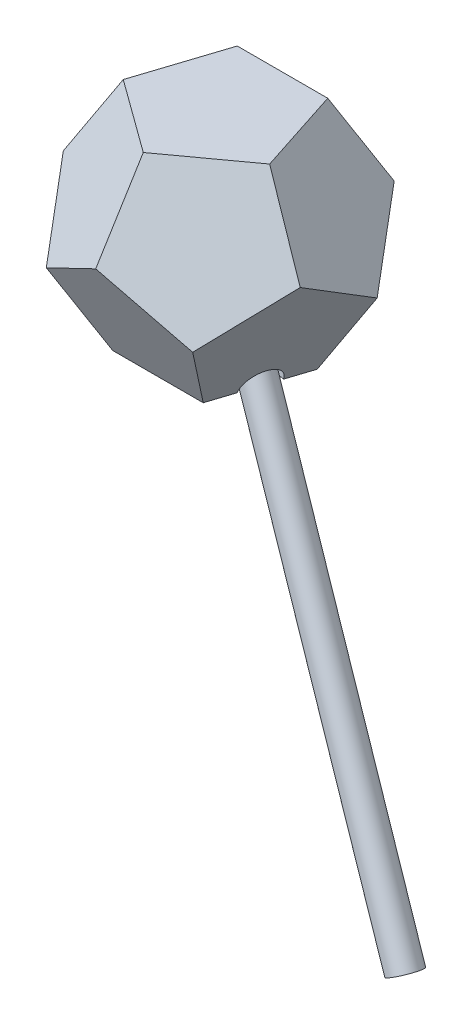
SolidWorks part; units mm, degrees
ref_plane "Front Plane" through (0, 0, 0) normal (0, 0, 1) x (1, 0, 0)
ref_plane "Top Plane" through (0, 0, 0) normal (0, 1, 0) x (1, 0, 0)
ref_plane "Right Plane" through (0, 0, 0) normal (1, 0, 0) x (0, 0, -1)
sketch "Sketch1" plane through (0, 0, 0) normal (0, 1, 0) x (1, 0, 0)
  line L1 (0, 17.013) -> (-16.1803, 5.2573)
  line L2 (-16.1803, 5.2573) -> (-10, -13.7638)
  line L3 (-10, -13.7638) -> (10, -13.7638)
  line L4 (10, -13.7638) -> (16.1803, 5.2573)
  line L5 (16.1803, 5.2573) -> (0, 17.013)
  circle A0 centre (0, 0) radius 13.7638 construction
  dimension "D1" = 20
extrude "Boss-Extrude1" add sketch "Sketch1" along normal blind 44.54 draft 26.57
ref_plane "Plane3" through (0, 22.27, 0) normal (0, 1, 0) x (1, 0, 0)
sketch "Sketch18" plane through (0, 22.27, 0) normal (0, 1, 0) x (1, 0, 0)
  line L0 (0, 0) -> (0, 44.5462)
  line L1 (0, 44.5462) -> (-42.3659, 13.7655) construction
  line L2 (42.3659, 13.7655) -> (0, 44.5462) construction
  line L3 (0, 0) -> (3.1668, 9.7464)
  line L4 (10, -13.7638) -> (16.1803, 5.2573) construction
sketch "Sketch2" plane through (0, 44.54, 0) normal (0, 1, 0) x (1, 0, 0)
  line L1 (0, -17.013) -> (16.1803, -5.2573)
  line L2 (16.1803, -5.2573) -> (10, 13.7638)
  line L3 (10, 13.7638) -> (-10, 13.7638)
  line L4 (-10, 13.7638) -> (-16.1803, -5.2573)
  line L5 (-16.1803, -5.2573) -> (0, -17.013)
  circle A0 centre (0, 0) radius 13.7638 construction
  dimension "D1" = 20
extrude "Cut-Extrude1" cut sketch "Sketch2" against normal blind 44.54 draft 26.57 flip side to cut
ref_plane "Plane1" through (3.6175, -6.1551, 1.1754) normal (0.5, -0.8507, 0.1624) x (0.4408, 0.0885, -0.8932)
sketch "Sketch3" plane through (3.6175, -6.1551, 1.1754) normal (0.5, -0.8507, 0.1624) x (0.4408, 0.0885, -0.8932)
  line L0 (-7.8859, 13.2251) -> (11.8286, 9.8577) construction
  circle A0 centre (1.9714, 11.5414) radius 4.05
  dimension "D1" = 8.1
extrude "Cut-Extrude2" cut sketch "Sketch3" against normal blind 35 contours A0
sketch "Sketch4" plane through (-13.8812, 23.6185, -4.5103) normal (0.5, -0.8507, 0.1624) x (0.866, 0.4911, -0.0938)
  circle A0 centre (10.9378, 4.1778) radius 3.2928
extrude "Boss-Extrude2" add sketch "Sketch4" along normal blind 130
sketch "Sketch5" [suppressed] plane through (51.1142, -86.9691, 16.608) normal (0.5, -0.8507, 0.1624) x (0.866, 0.4911, -0.0938)
  point P0 (10.9378, 4.1778)
  point P1 (24.3327, -4.2864)
sketch "Sketch6" plane through (-6.4716, -5.5062, -8.9074) normal (-0.5257, -0.4473, -0.7236) x (-0.8507, 0.2764, 0.4472)
  line L0 (-5.2301, 8.173) -> (2.5982, 32.2619) construction
  line L1 (2.5982, 32.2619) -> (16.8638, 27.6259) construction
  line L2 (16.8638, 27.6259) -> (9.0355, 3.537) construction
  line L3 (-7.6077, 8.9457) -> (11.4131, 2.7644) construction
  line L4 (11.4149, 35.1253) -> (23.1714, 18.9448) construction
  line L5 (1.3421, 28.3966) -> (15.6077, 23.7606)
  line L6 (15.6077, 23.7606) -> (10.9717, 9.495)
  line L7 (10.9717, 9.495) -> (-3.2939, 14.131)
  line L8 (-3.2939, 14.131) -> (1.3421, 28.3966)
  line L9 (6.1548, 18.9465) -> (-7.6077, 28.9473) construction
  line L10 (11.4149, 35.1253) -> (6.1548, 18.9465) construction
  line L11 (6.1548, 18.9465) -> (-7.6077, 8.9457) construction
  line L12 (-0.9759, 21.2638) -> (13.2897, 16.6278) construction
  dimension "D1" = 15
  dimension "D2" = 2.5
  dimension "D3" = 15
ref_plane "Plane2" through (-9.4711, 16.1166, -3.0773) normal (-0.4999, 0.8507, -0.1624) x (0.8661, 0.4911, -0.0938)
sketch "Sketch7" plane through (-10.4712, -5.5062, 3.4023) normal (-0.8506, -0.4473, 0.2764) x (0.2446, 0.1286, 0.961)
  line L0 (2.8652, 19.7147) -> (-12.3923, 27.2443) construction
  line L1 (2.8652, 19.7147) -> (-9.0106, 7.5307) construction
  line L2 (10.7815, 4.6542) -> (2.8652, 19.7147) construction
  line L3 (-9.0106, 7.5307) -> (10.7815, 4.6542) construction
  line L4 (-5.1697, 30.4822) -> (-7.9023, 11.6798)
  line L5 (-7.9023, 11.6798) -> (10.9001, 8.9472)
  line L6 (10.9001, 8.9472) -> (13.6328, 27.7496)
  line L7 (13.6328, 27.7496) -> (-5.1697, 30.4822)
  line L8 (2.8652, 19.7147) -> (5.3119, 36.5495) construction
  circle A0 centre (2.8652, 19.7147) radius 9.5 construction
  dimension "D1" = 19
sketch "Sketch8" plane through (0, -5.5062, 11.0101) normal (0, -0.4473, 0.8944) x (1, 0, 0)
  line L0 (0, 36.9335) -> (0, 19.9204) construction
  line L1 (0, 19.9204) -> (-10, 6.1564) construction
  line L2 (10, 6.1564) -> (0, 19.9204) construction
sketch "Sketch10" plane through (10.4712, -5.5062, 3.4023) normal (0.8506, -0.4473, 0.2764) x (0.2446, -0.1286, -0.961)
  line L0 (-5.3119, 36.5495) -> (-2.865, 19.7133) construction
  line L1 (-2.865, 19.7133) -> (-10.7815, 4.6542) construction
  line L2 (-2.865, 19.7133) -> (9.0106, 7.5307) construction
sketch "Sketch11" plane through (6.4716, -5.5062, -8.9074) normal (0.5257, -0.4473, -0.7236) x (-0.8507, -0.2764, -0.4472)
  line L0 (-11.4149, 35.1253) -> (-6.1567, 18.9451) construction
  line L1 (-6.1567, 18.9451) -> (-11.4131, 2.7644) construction
  line L2 (-6.1567, 18.9451) -> (7.6077, 8.9457) construction
sketch "Sketch12" plane through (0, 14.4173, -28.8284) normal (0, 0.4473, -0.8944) x (-1, 0, 0)
  line L0 (0, 2.9026) -> (0, 19.9157)
  line L1 (0, 19.9157) -> (-10, 33.6796)
  line L2 (0, 19.9157) -> (10, 33.6796)
sketch "Sketch13" plane through (-27.4174, 14.4173, -8.9085) normal (-0.8506, 0.4473, -0.2764) x (-0.2446, 0.1286, 0.961)
  line L0 (0.4175, 2.8724) -> (2.8643, 19.7086)
  line L1 (2.8643, 19.7086) -> (-5.0521, 34.7677)
  line L2 (2.8643, 19.7086) -> (14.7399, 31.8913)
sketch "Sketch14" plane through (-16.9449, 14.4173, 23.3227) normal (-0.5257, 0.4473, 0.7236) x (0.8507, 0.2764, 0.4472)
  line L0 (0.8971, 2.7605) -> (6.1552, 18.9406)
  line L1 (6.1552, 18.9406) -> (0.8988, 35.1214)
  line L2 (19.9196, 28.9401) -> (6.1552, 18.9406)
sketch "Sketch15" plane through (16.9449, 14.4173, 23.3227) normal (0.5257, 0.4473, 0.7236) x (0.8507, -0.2764, -0.4472)
  line L0 (-0.8988, 35.1214) -> (-6.1552, 18.9406)
  line L1 (-6.1552, 18.9406) -> (-19.9196, 28.9401)
  line L2 (-6.1552, 18.9406) -> (-0.8971, 2.7605)
sketch "Sketch16" plane through (27.4174, 14.4173, -8.9085) normal (0.8506, 0.4473, -0.2764) x (-0.2446, -0.1286, -0.961)
  line L0 (-14.7399, 31.8913) -> (-2.8643, 19.7086)
  line L1 (-2.8643, 19.7086) -> (5.0521, 34.7677)
  line L2 (-2.8643, 19.7086) -> (-0.4175, 2.8724)
sketch "Sketch17" plane through (0, 44.54, 0) normal (0, 1, 0) x (1, 0, 0)
  line L0 (0, -17.013) -> (0, 0) construction
  line L1 (0, 0) -> (10, 13.7638) construction
sketch "Sketch19" plane through (0, 0, 0) normal (0, -1, 0) x (1, 0, 0)
  line L0 (0, 0) -> (10, 13.7638)
sketch "Sketch20" plane through (0, 14.4173, -28.8284) normal (0, 0.4473, -0.8944) x (-1, 0, 0)
  point P0 (0, 19.9981)
sketch "Sketch21" plane through (0, 14.4173, -28.8284) normal (0, 0.4473, -0.8944) x (-1, 0, 0)
  line L0 (-16.1818, 14.6573) -> (0, 19.918) construction
  line L1 (0, 19.918) -> (0, 2.9026) construction
  line L2 (0, 2.9026) -> (16.1818, 14.6573) construction
  line L3 (-16.1818, 14.6573) -> (0, 2.9026) construction
  line L4 (16.1818, 14.6573) -> (0, 19.918) construction
sketch "Sketch22" plane through (-6.4716, -5.5062, -8.9074) normal (-0.5257, -0.4473, -0.7236) x (-0.8507, 0.2764, 0.4472)
  line L0 (-7.6077, 8.9457) -> (6.1571, 18.9465) construction
  line L1 (6.1571, 18.9465) -> (11.4131, 2.7644) construction
  line L2 (6.1571, 18.9465) -> (23.1714, 18.9448) construction
sketch "Sketch23" plane through (0, 0, 0) normal (1, 0, 0) x (0, 0, -1)
  line L0 (0, 22.27) -> (19.9203, 32.2297)
  line L1 (0, 22.27) -> (44.5462, 22.27) construction
  line L2 (0, 22.27) -> (0, 27.2498)
sketch "Sketch24" plane through (51.1142, -86.9691, 16.608) normal (0.5, -0.8507, 0.1624) x (0.866, 0.4911, -0.0938)
  point P0 (10.9378, 4.1778)
